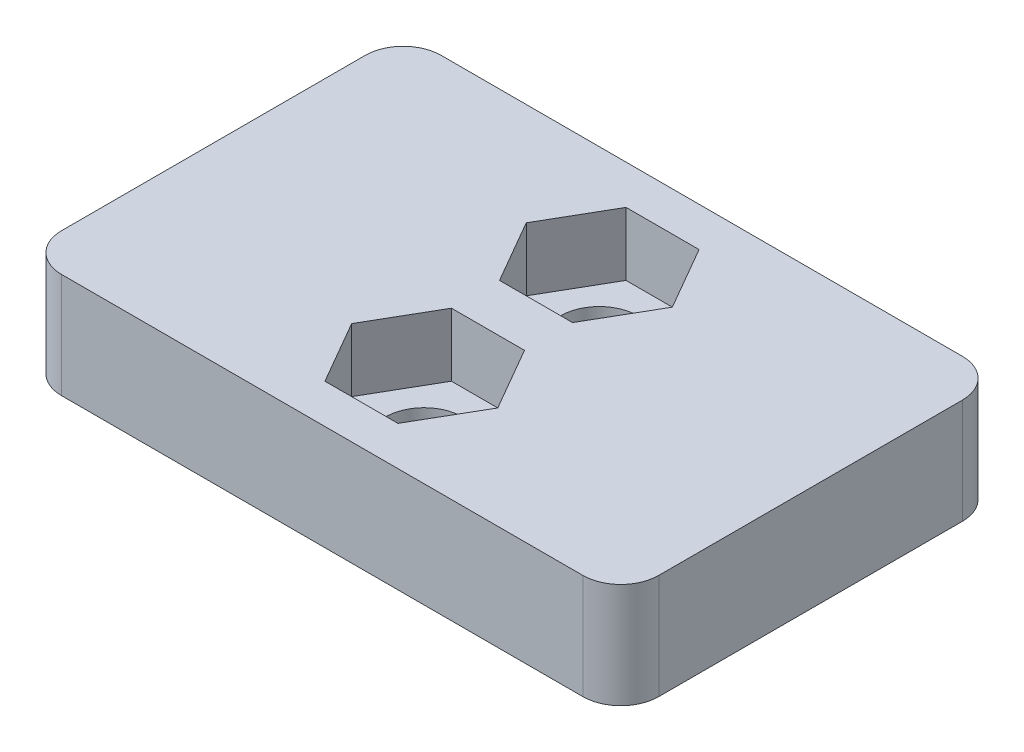
SolidWorks part; units mm, degrees
ref_plane "Plan de face" through (0, 0, 0) normal (0, 0, 1) x (1, 0, 0)
ref_plane "Plan de dessus" through (0, 0, 0) normal (0, 1, 0) x (1, 0, 0)
ref_plane "Plan de droite" through (0, 0, 0) normal (1, 0, 0) x (0, 0, -1)
sketch "Esquisse2" plane through (0, 0, 0) normal (0, 0, 1) x (1, 0, 0)
  line L1 (8.7419, 23.2683) -> (55.9419, 23.2683)
  line L2 (8.7419, 23.2683) -> (8.7419, 4.9683)
  line L3 (8.7419, 4.9683) -> (55.9419, 4.9683)
  line L4 (55.9419, 23.2683) -> (55.9419, 4.9683)
  dimension "D1" = 47.2
  dimension "D2" = 18.3
extrude "Boss.-Extru.3" add sketch "Esquisse2" along normal blind 30
sketch "Esquisse3" plane through (0, 23.2683, 0) normal (0, 1, 0) x (1, 0, 0)
  line L1 (38.1154, -8.1) -> (35.2287, -3.1)
  line L2 (35.2287, -3.1) -> (29.4552, -3.1)
  line L3 (29.4552, -3.1) -> (26.5684, -8.1)
  line L4 (26.5684, -8.1) -> (29.4552, -13.1)
  line L5 (29.4552, -13.1) -> (35.2287, -13.1)
  line L6 (35.2287, -13.1) -> (38.1154, -8.1)
  line L7 (38.1154, -21.9) -> (35.2287, -16.9)
  line L8 (35.2287, -16.9) -> (29.4552, -16.9)
  line L9 (29.4552, -16.9) -> (26.5684, -21.9)
  line L10 (26.5684, -21.9) -> (29.4552, -26.9)
  line L11 (29.4552, -26.9) -> (35.2287, -26.9)
  line L12 (35.2287, -26.9) -> (38.1154, -21.9)
  line L14 (55.9419, -30) -> (55.9419, 0) construction
  line L15 (55.9419, -30) -> (8.7419, -30) construction
  line L16 (55.9419, 0) -> (8.7419, 0) construction
  circle A0 centre (32.3419, -8.1) radius 5 construction
  circle A1 centre (32.3419, -21.9) radius 5 construction
  dimension "D1" = 10
  dimension "D2" = 10
  dimension "D3" = 23.6
  dimension "D4" = 23.6
  dimension "D5" = 8.1
  dimension "D6" = 8.1
extrude "Enlèv. mat.-Extru.1" cut sketch "Esquisse3" against normal blind 5
sketch "Esquisse6" plane through (0, 23.2683, 0) normal (0, 1, 0) x (1, 0, 0)
  line L0 (35.2287, -16.9) -> (29.4552, -16.9) construction
  circle A0 centre (32.3419, -8.1) radius 3.05
  circle A1 centre (32.3419, -21.95) radius 3.05
  dimension "D2" = 6.1
  dimension "D3" = 6.1
  dimension "D1" = 5.05
extrude "Enlèv. mat.-Extru.2" cut sketch "Esquisse6" against normal blind 29
fillet "Congé1" radius 3 4 edges at (55.9419, 14.1183, 30) (8.7419, 14.1183, 30) (8.7419, 14.1183, 0) (55.9419, 14.1183, 0)
sketch "Esquisse7" plane through (0, 4.9683, 0) normal (0, -1, 0) x (1, 0, 0)
  line L1 (7.4698, 31.7963) -> (63.6789, 31.7963)
  line L2 (7.4698, 31.7963) -> (7.4698, -3.2912)
  line L3 (7.4698, -3.2912) -> (63.6789, -3.2912)
  line L4 (63.6789, 31.7963) -> (63.6789, -3.2912)
extrude "Enlèv. mat.-Extru.3" cut sketch "Esquisse7" against normal blind 10
equation "\"10pmm\"=11"
